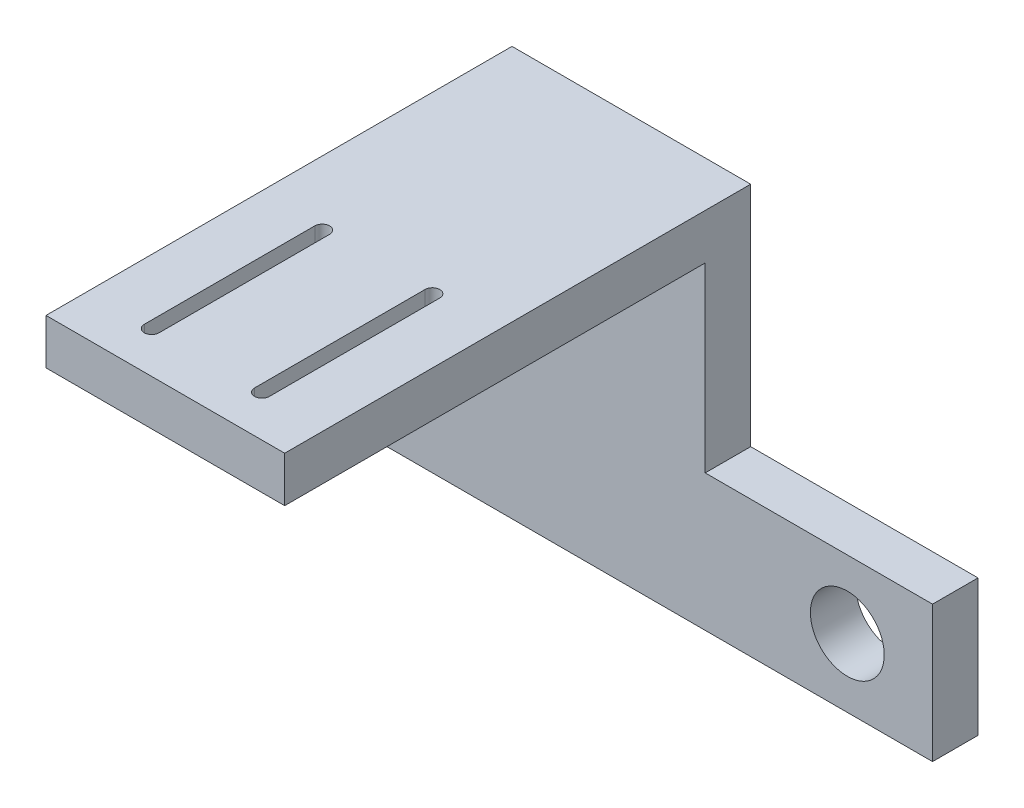
SolidWorks part; units mm, degrees
ref_plane "Front Plane" through (0, 0, 0) normal (0, 0, 1) x (1, 0, 0)
ref_plane "Top Plane" through (0, 0, 0) normal (0, 1, 0) x (1, 0, 0)
ref_plane "Right Plane" through (0, 0, 0) normal (1, 0, 0) x (0, 0, -1)
sketch "Sketch1" plane through (0, 0, 0) normal (0, 0, 1) x (1, 0, 0)
  line L0 (30.5, 12) -> (30.5, 0) construction
  line L1 (0, 0) -> (61, 0)
  line L2 (0, 0) -> (0, 12)
  line L3 (0, 12) -> (61, 12)
  line L4 (61, 0) -> (61, 12)
  circle A4 centre (7.5, 6) radius 3.25
  circle A5 centre (53.5, 6) radius 3.25
  point P5 (7.5, 6)
  point P6 (53.5, 6)
  point P11 (0, 0)
  point P12 (7.5, 7.2887)
  point P15 (0, 0)
  point P16 (30.5, 6)
  dimension "D4" = 7.5
  dimension "D2" = 6.5
  dimension "D1" = 46
  dimension "D3" = 12
extrude "Boss-Extrude1" add sketch "Sketch1" along normal blind 4
sketch "Sketch3" plane through (0, 0, 0) normal (-1, 0, 0) x (0, 0, 1)
  line L0 (4, 12) -> (4, 28)
  line L1 (4, 28) -> (41, 28)
  line L2 (41, 28) -> (41, 32)
  line L3 (41, 32) -> (0, 32)
  line L4 (0, 32) -> (0, 12)
  line L5 (0, 12) -> (4, 12)
  point P3 (0, 27.6111)
  dimension "D1" = 16
  dimension "D2" = 41
extrude "Boss-Extrude2" add sketch "Sketch3" against normal blind 21 from offset 20 offset against normal yes
sketch "Sketch4" plane through (0, 32, 0) normal (0, 1, 0) x (1, 0, 0)
  line L0 (35.35, -22.35) -> (35.35, -37.35) construction
  line L1 (36, -22.35) -> (36, -37.35)
  line L2 (34.7, -22.35) -> (34.7, -37.35)
  line L3 (25.65, -22.35) -> (25.65, -37.35) construction
  line L4 (26.3, -22.35) -> (26.3, -37.35)
  line L5 (25, -22.35) -> (25, -37.35)
  line L11 (30.5, -41) -> (30.5, 0) construction
  line L12 (41, -41) -> (20, -41) construction
  line L13 (41, 0) -> (20, 0) construction
  arc A0 (36, -22.35) -> (34.7, -22.35) centre (35.35, -22.35) ccw
  arc A1 (34.7, -37.35) -> (36, -37.35) centre (35.35, -37.35) ccw
  arc A2 (26.3, -22.35) -> (25, -22.35) centre (25.65, -22.35) ccw
  arc A3 (25, -37.35) -> (26.3, -37.35) centre (25.65, -37.35) ccw
  point P2 (35.35, -29.85)
  point P7 (25.65, -29.85)
  point P14 (25.65, -25.5)
  point P15 (0, 0)
  point P16 (25.65, -29.4271)
  point P17 (25.65, -27.15)
  point P18 (26.5, -27.15)
  point P19 (34.5, -27.15)
  point P20 (35.35, -27.15)
  point P21 (35.35, -37.15)
  point P22 (35.35, -32.15)
  point P23 (0, 0)
  dimension "D4" = 3
  dimension "D1" = 1.3
  dimension "D2" = 9.7
  dimension "D3" = 15
extrude "Cut-Extrude1" cut sketch "Sketch4" against normal up to next
